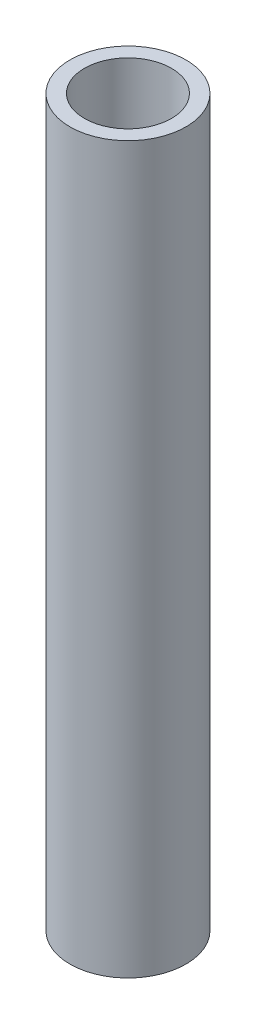
SolidWorks part; units mm, degrees
ref_plane "Front Plane" through (0, 0, 0) normal (0, 0, 1) x (1, 0, 0)
ref_plane "Top Plane" through (0, 0, 0) normal (0, 1, 0) x (1, 0, 0)
ref_plane "Right Plane" through (0, 0, 0) normal (1, 0, 0) x (0, 0, -1)
sketch "Sketch1" plane through (0, 0, 0) normal (0, 1, 0) x (1, 0, 0)
  circle A0 centre (0, 0) radius 6
  circle A1 centre (0, 0) radius 8
  dimension "D1" = 16
  dimension "D2" = 2
extrude "Boss-Extrude1" add sketch "Sketch1" along normal mid plane 100
